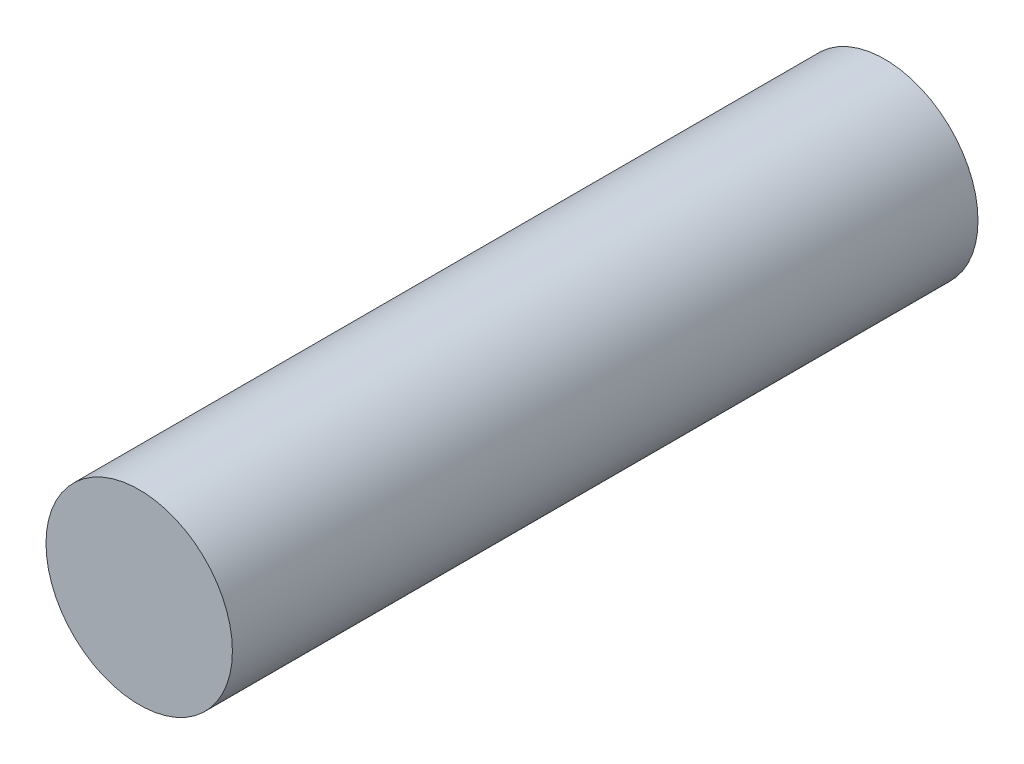
SolidWorks part; units mm, degrees
ref_plane "Front Plane" through (0, 0, 0) normal (0, 0, 1) x (1, 0, 0)
ref_plane "Top Plane" through (0, 0, 0) normal (0, 1, 0) x (1, 0, 0)
ref_plane "Right Plane" through (0, 0, 0) normal (1, 0, 0) x (0, 0, -1)
sketch "Sketch1" plane through (0, 0, 0) normal (0, 0, 1) x (1, 0, 0)
  circle A0 centre (0, 0) radius 4.7625
  dimension "D1" = 9.525
extrude "Boss-Extrude1" add sketch "Sketch1" along normal blind 38.1
equation "\"Wheel Thickness\"= 1in"
equation "\"Wheel Diameter\"= 3in"
equation "\"Motor Rear Diameter\" = 36.2mm"
equation "\"Motor Front Diameter\" = 12mm"
equation "\"Material Thickness\" = .25in"
equation "\"Wheel Cutout Diameter\"= 2cm"
equation "\"Motor Mount Tab Thickness\" = 100mm"
equation "\"Motor Mount Tab Height\" = 40mm"
equation "\"Motor Shaft Diameter\" = 3mm"
equation "\"Wheel Radius Clearance\" = 5mm"
equation "\"Wheel Cutout Width\" = 1.5in"
equation "\"Base Diameter\" = 10in"
equation "\"Wheel Mount Distance\" = 5mm"
equation "\"Motor Mount Distance\" = 50mm"
equation "\"Motor Cutout Length\" = 6in"
equation "\"Rod Diameter\" = 3/8in"
equation "\"D1@Sketch1\"=\"Rod Diameter\""
equation "\"Rod Length\" = 1.5in"
equation "\"D1@Boss-Extrude1\"=\"Rod Length\""
